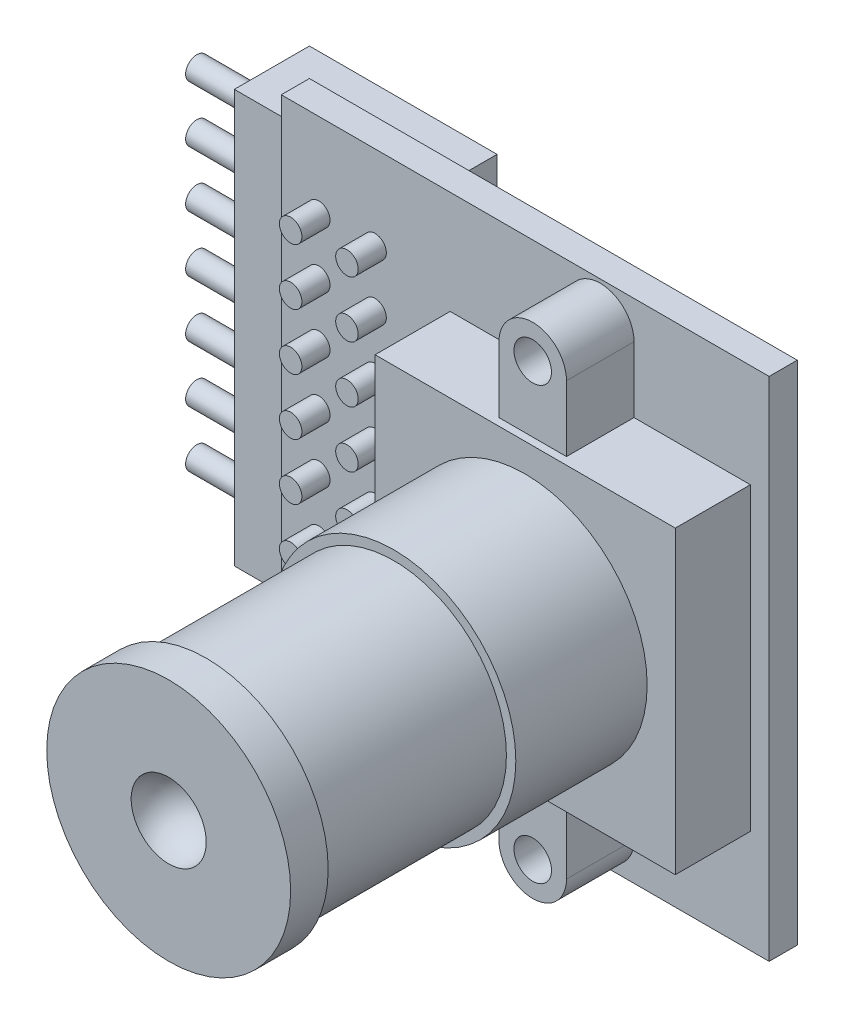
SolidWorks part; units mm, degrees
ref_plane "前视基准面" through (0, 0, 0) normal (0, 0, 1) x (1, 0, 0)
ref_plane "上视基准面" through (0, 0, 0) normal (0, 1, 0) x (1, 0, 0)
ref_plane "右视基准面" through (0, 0, 0) normal (1, 0, 0) x (0, 0, -1)
sketch "草图1" plane through (0, 0, 0) normal (0, 0, 1) x (1, 0, 0)
  line L1 (-8, -8) -> (8, -8)
  line L2 (-8, -8) -> (-8, 8)
  line L3 (-8, 8) -> (8, 8)
  line L4 (8, -8) -> (8, 8)
  line L5 (-8, -8) -> (8, 8) construction
  line L6 (-8, 8) -> (8, -8) construction
  point P0 (0, 0)
  dimension "D1" = 16
  dimension "D2" = 16
extrude "凸台-拉伸1" add sketch "草图1" along normal blind 4
sketch "草图2" plane through (0, 0, 4) normal (0, 0, 1) x (1, 0, 0)
  circle A0 centre (0, 0) radius 6.5
extrude "凸台-拉伸2" add sketch "草图2" along normal blind 7
sketch "草图3" plane through (0, 0, 11) normal (0, 0, 1) x (1, 0, 0)
  circle A0 centre (0, 0) radius 6
extrude "凸台-拉伸3" add sketch "草图3" along normal blind 12
sketch "草图4" plane through (0, 0, 23) normal (0, 0, 1) x (1, 0, 0)
  circle A0 centre (0, 0) radius 6.5
extrude "凸台-拉伸4" add sketch "草图4" against normal blind 2
sketch "草图5" plane through (0, 0, 23) normal (0, 0, 1) x (1, 0, 0)
  line L0 (0, 2) -> (0, -2) construction
  line L1 (0, 2) -> (0, -2)
  arc A0 (0, -2) -> (0, 2) centre (0, 0) ccw
revolve "切除-旋转2" cut sketch "草图5" angle 360 about L0
sketch "草图6" plane through (0, 0, 0) normal (0, 0, -1) x (-1, 0, 0)
  line L0 (0, 4.5) -> (0, 11.5) construction
  line L1 (-8, 8) -> (8, 8) construction
  line L2 (-1.8, 8) -> (-1.8, 11.5)
  line L3 (1.8, 8) -> (1.8, 11.5)
  line L4 (0, 0) -> (10.6685, 0) construction
  line L5 (-1.8, 8) -> (1.8, 8)
  line L6 (-1.8, -8) -> (1.8, -8)
  line L7 (1.8, -8) -> (1.8, -11.5)
  line L8 (-1.8, -8) -> (-1.8, -11.5)
  circle A0 centre (0, 11.5) radius 1
  arc A1 (1.8, 11.5) -> (-1.8, 11.5) centre (0, 11.5) ccw
  arc A2 (1.8, -11.5) -> (-1.8, -11.5) centre (0, -11.5) cw
  circle A3 centre (0, -11.5) radius 1
  point P5 (0, 8)
  point P18 (0, -8)
  dimension "D2" = 1.8
  dimension "D1" = 3.5
extrude "凸台-拉伸5" add sketch "草图6" against normal blind 3.6
sketch "草图7" plane through (0, 0, 0) normal (0, 0, -1) x (-1, 0, 0)
  line L0 (-11.0874, 0) -> (12.7386, 0) construction
  line L1 (-9, 13.5) -> (17, 13.5)
  line L2 (-9, 13.5) -> (-9, -13.5)
  line L3 (-9, -13.5) -> (17, -13.5)
  line L4 (17, 13.5) -> (17, -13.5)
  line L5 (-9, 13.5) -> (17, -13.5) construction
  line L6 (-9, -13.5) -> (17, 13.5) construction
  line L7 (-8, -8) -> (-8, 8) construction
  point P4 (4, 0)
  point P8 (-4.023, 0)
  point P9 (3.6082, 0)
  dimension "D1" = 27
  dimension "D2" = 26
  dimension "D3" = 1
extrude "凸台-拉伸6" add sketch "草图7" along normal blind 1.5
sketch "草图8" plane through (0, 0, -1.5) normal (0, 0, -1) x (-1, 0, 0)
  line L0 (0, 0) -> (25.7993, 0) construction
  line L1 (11, -11) -> (21, -11)
  line L2 (11, -11) -> (11, 11)
  line L3 (11, 11) -> (21, 11)
  line L4 (21, -11) -> (21, 11)
  line L5 (11, -11) -> (21, 11) construction
  line L6 (11, 11) -> (21, -11) construction
  line L7 (17, -13.5) -> (17, 13.5) construction
  point P0 (16, 0)
  point P5 (15.4277, 0)
  point P9 (16.1764, 0)
  dimension "D1" = 10
  dimension "D2" = 4
extrude "凸台-拉伸7" add sketch "草图8" along normal blind 4
sketch "草图9" plane through (-21, 0, 0) normal (-1, 0, 0) x (0, 0, 1)
  line L0 (-3.5, 11) -> (-3.5, -11) construction
  line L1 (-5.5, 11) -> (-1.5, 11) construction
  line L2 (-5.5, -11) -> (-1.5, -11) construction
  line L3 (-3.5, 0) -> (0, 0) construction
  circle A0 centre (-3.5, 0) radius 0.6
  circle A1 centre (-3.5, 3) radius 0.6
  circle A2 centre (-3.5, 6) radius 0.6
  circle A3 centre (-3.5, 9) radius 0.6
  circle A4 centre (-3.5, -9) radius 0.6
  circle A5 centre (-3.5, -6) radius 0.6
  circle A6 centre (-3.5, -3) radius 0.6
  dimension "D1" = 4
extrude "凸台-拉伸8" add sketch "草图9" along normal blind 4
sketch "草图10" plane through (0, 0, 0) normal (0, 0, 1) x (1, 0, 0)
  line L0 (-12, 9) -> (-12, -9) construction
  line L1 (-17, -11) -> (-17, 11) construction
  circle A0 centre (-12, 9) radius 0.6
  circle A1 centre (-15, 9) radius 0.6
  circle A2 centre (-15, 6) radius 0.6
  circle A3 centre (-15, 3) radius 0.6
  circle A4 centre (-15, 0) radius 0.6
  circle A5 centre (-15, -3) radius 0.6
  circle A6 centre (-15, -6) radius 0.6
  circle A7 centre (-15, -9) radius 0.6
  circle A8 centre (-12, 6) radius 0.6
  circle A9 centre (-12, 3) radius 0.6
  circle A10 centre (-12, 0) radius 0.6
  circle A11 centre (-12, -3) radius 0.6
  circle A12 centre (-12, -6) radius 0.6
  circle A13 centre (-12, -9) radius 0.6
  point P4 (-17, 0)
  dimension "D2" = 2
  dimension "D1" = 5
  dimension "D3" = 7
extrude "凸台-拉伸9" add sketch "草图10" along normal blind 1.5
sketch "草图11" plane through (0, 0, 0) normal (0, 0, 1) x (1, 0, 0)
  line L1 (-8.8674, -11.918) -> (-4.7188, -11.918)
  line L2 (-8.8674, -11.918) -> (-8.8674, -8.8253)
  line L3 (-8.8674, -8.8253) -> (-4.7188, -8.8253)
  line L4 (-4.7188, -11.918) -> (-4.7188, -8.8253)
  line L5 (-8.8674, -11.918) -> (-4.7188, -8.8253) construction
  line L6 (-8.8674, -8.8253) -> (-4.7188, -11.918) construction
  point P0 (-6.7931, -10.3717)
extrude "凸台-拉伸10" add sketch "草图11" along normal blind 1.5
